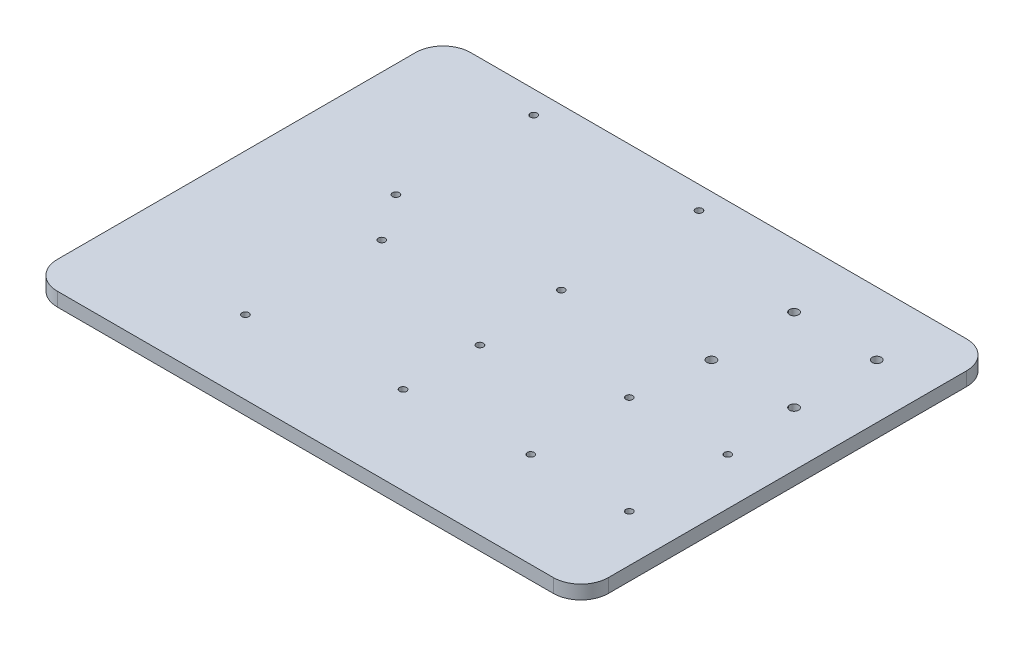
SolidWorks part; units mm, degrees
ref_plane "Front Plane" through (0, 0, 0) normal (0, 0, 1) x (1, 0, 0)
ref_plane "Top Plane" through (0, 0, 0) normal (0, 1, 0) x (1, 0, 0)
ref_plane "Right Plane" through (0, 0, 0) normal (1, 0, 0) x (0, 0, -1)
sketch "Sketch1" plane through (0, 0, 0) normal (0, 1, 0) x (1, 0, 0)
  line L1 (-90, -75) -> (90, -75)
  line L2 (-100, -65) -> (-100, 65)
  line L3 (-90, 75) -> (90, 75)
  line L4 (100, -65) -> (100, 65)
  line L5 (-100, -75) -> (100, 75) construction
  line L6 (-100, 75) -> (100, -75) construction
  arc A0 (90, -75) -> (100, -65) centre (90, -65) ccw
  arc A1 (-90, -75) -> (-100, -65) centre (-90, -65) cw
  arc A2 (-100, 65) -> (-90, 75) centre (-90, 65) cw
  arc A3 (90, 75) -> (100, 65) centre (90, 65) cw
  point P1 (0, 0)
  dimension "D3" = 10
  dimension "D1" = 200
  dimension "D2" = 150
extrude "Boss-Extrude1" add sketch "Sketch1" along normal blind 5 contours L2 A2 L3 A3 L4 A0 L1 A1
hole_wizard "arduino uno holes" positions "Sketch3" profile "Sketch2" tap size "M3x0.5" standard "ANSI Metric" end condition through all
sketch "Sketch3" plane through (0, 5, 0) normal (0, 1, 0) x (1, 0, 0)
  point P0 (3.609, -15.2498)
  point P2 (3.609, -43.1498)
  point P4 (-47.191, -0.0498)
  point P6 (-48.491, -48.2498)
  dimension "D1" = 27.9
  dimension "D2" = 15.2
  dimension "D3" = 50.8
  dimension "D4" = 1.3
  dimension "D5" = 5.1
sketch "Sketch2" plane through (3.609, 5, 15.2498) normal (1, 0, 0) x (0, 0, 1)
  line L0 (0, 0) -> (0, 5)
  line L1 (0, 5) -> (1.25, 5)
  line L2 (1.25, 5) -> (1.25, 0)
  line L5 (1.25, 0) -> (0, 0)
  line L11 (0, -6.35) -> (0, 107.95) construction
  dimension "Thru Tap Drill Dia." = 2.5
  dimension "Thru Tap Drill Depth" = 5
cosmetic thread "Hole Thread1" parameters "D2"=3
cosmetic thread "Hole Thread2" parameters "D2"=3
cosmetic thread "Hole Thread3" parameters "D2"=3
cosmetic thread "Hole Thread4" parameters "D2"=3
hole_wizard "l298n holes" positions "Sketch16" profile "Sketch17" tap size "M3x0.5" standard "ANSI Metric" end condition through all
sketch "Sketch16" plane through (0, 5, 0) normal (0, 1, 0) x (1, 0, 0)
  point P0 (47.2019, -40.4092)
  point P6 (82.9619, -40.4092)
  point P7 (82.9619, -4.6492)
  point P8 (47.2019, -4.6492)
  dimension "D1" = 2
  dimension "D2" = 2
sketch "Sketch17" plane through (47.2019, 5, 40.4092) normal (1, 0, 0) x (0, 0, 1)
  line L0 (0, 0) -> (0, 5)
  line L1 (0, 5) -> (1.25, 5)
  line L2 (1.25, 5) -> (1.25, 0)
  line L5 (1.25, 0) -> (0, 0)
  line L11 (0, -6.35) -> (0, 107.95) construction
  dimension "Thru Tap Drill Dia." = 2.5
  dimension "Thru Tap Drill Depth" = 5
cosmetic thread "Hole Thread25" parameters "D2"=3
cosmetic thread "Hole Thread26" parameters "D2"=3
cosmetic thread "Hole Thread27" parameters "D2"=3
cosmetic thread "Hole Thread28" parameters "D2"=3
hole_wizard "motor mounting bracket holes" positions "Sketch18" profile "Sketch19" tap size "M4x0.7" standard "ANSI Metric" end condition through all
sketch "Sketch18" plane through (0, 5, 0) normal (0, 1, 0) x (1, 0, 0)
  point P0 (50.273, 22.0978)
  point P5 (80.273, 22.0978)
  point P6 (80.273, 52.0978)
  point P7 (50.273, 52.0978)
  dimension "D1" = 2
  dimension "D2" = 2
sketch "Sketch19" plane through (50.273, 5, -22.0978) normal (1, 0, 0) x (0, 0, 1)
  line L0 (0, 0) -> (0, 5)
  line L1 (0, 5) -> (1.65, 5)
  line L2 (1.65, 5) -> (1.65, 0)
  line L5 (1.65, 0) -> (0, 0)
  line L11 (0, -6.35) -> (0, 107.95) construction
  dimension "Thru Tap Drill Dia." = 3.3
  dimension "Thru Tap Drill Depth" = 5
cosmetic thread "Hole Thread29" parameters "D2"=4
cosmetic thread "Hole Thread30" parameters "D2"=4
cosmetic thread "Hole Thread35" parameters "D2"=4
cosmetic thread "Hole Thread36" parameters "D2"=4
hole_wizard "protoboard holes" positions "Sketch20" profile "Sketch21" tap size "M3x0.5" standard "ANSI Metric" end condition through all
sketch "Sketch20" plane through (0, 5, 0) normal (0, 1, 0) x (1, 0, 0)
  point P0 (-58.9099, 16.7748)
  point P6 (1.0901, 16.7748)
  point P7 (1.0901, 66.7748)
  point P8 (-58.9099, 66.7748)
  dimension "D1" = 2
  dimension "D2" = 2
sketch "Sketch21" plane through (-58.9099, 5, -16.7748) normal (1, 0, 0) x (0, 0, 1)
  line L0 (0, 0) -> (0, 5)
  line L1 (0, 5) -> (1.25, 5)
  line L2 (1.25, 5) -> (1.25, 0)
  line L5 (1.25, 0) -> (0, 0)
  line L11 (0, -6.35) -> (0, 107.95) construction
  dimension "Thru Tap Drill Dia." = 2.5
  dimension "Thru Tap Drill Depth" = 5
cosmetic thread "Hole Thread37" parameters "D2"=3
cosmetic thread "Hole Thread38" parameters "D2"=3
cosmetic thread "Hole Thread39" parameters "D2"=3
cosmetic thread "Hole Thread40" parameters "D2"=3
equation "\"w\"= 200"
equation "\"D1@Sketch1\"=\"w\""
equation "\"h\"= 150"
equation "\"D2@Sketch1\"=\"h\""
equation "\"th\"=5"
equation "\"D1@Boss-Extrude1\"=\"th\""
